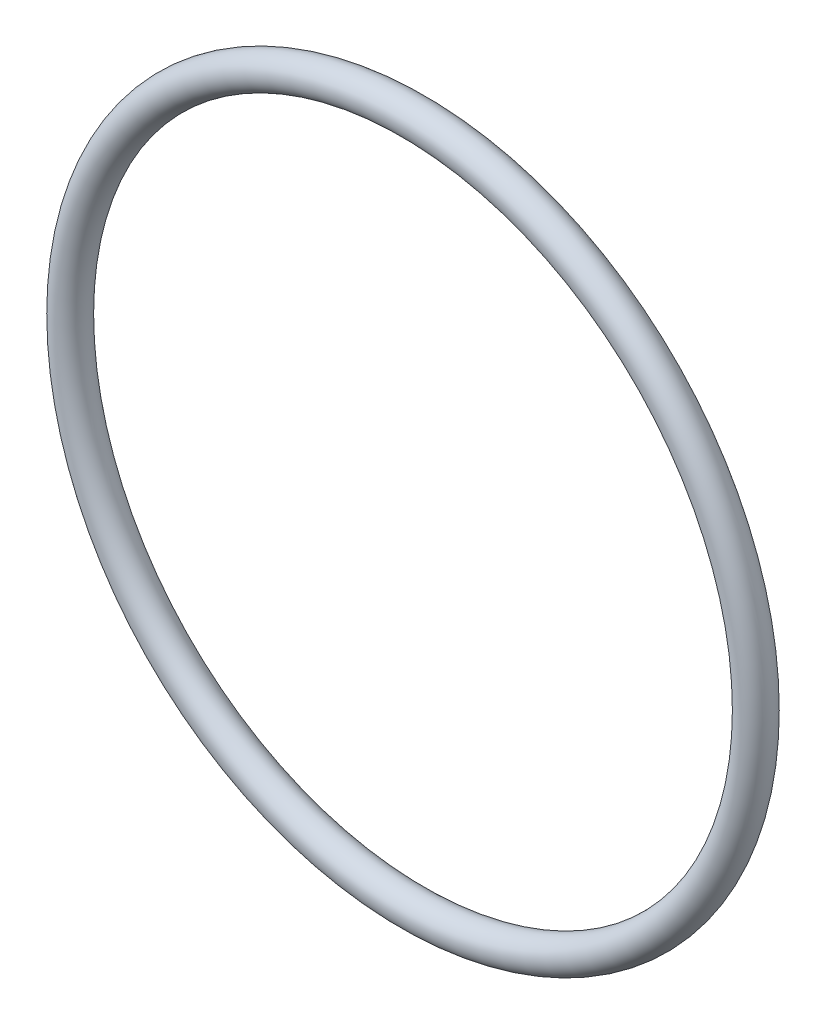
SolidWorks part; units mm, degrees
material "Rubber"
ref_plane "Front" through (0, 0, 0) normal (0, 0, 1) x (1, 0, 0)
ref_plane "Top" through (0, 0, 0) normal (0, 1, 0) x (1, 0, 0)
ref_plane "Right" through (0, 0, 0) normal (1, 0, 0) x (0, 0, -1)
sketch "Sketch1" plane through (0, 0, 0) normal (1, 0, 0) x (0, -1, 0)
  line L0 (0, -1.7653) -> (0, 1.7653) construction
  line L2 (-42.0776, 0) -> (42.0776, 0) construction
  line L3 (-34.7218, 0) -> (34.7218, 0) construction
  circle A0 centre (36.4871, 0) radius 1.7653
  point P9 (34.7218, 0)
  point P10 (38.2524, 0)
  point P13 (36.4871, 1.7653)
  point P14 (36.4871, -1.7653)
  dimension "Width" = 3.5306
  dimension "ID" = 69.4436
revolve "Revolve1" add sketch "Sketch1" angle 360 about L0
